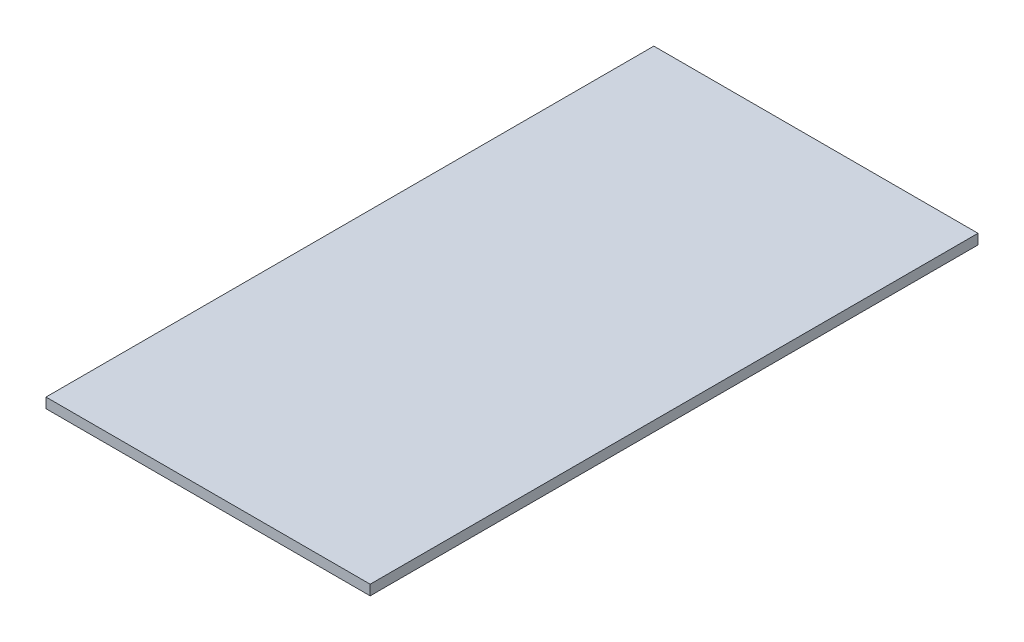
SolidWorks part; units mm, degrees
ref_plane "Front Plane" through (0, 0, 0) normal (0, 0, 1) x (1, 0, 0)
ref_plane "Top Plane" through (0, 0, 0) normal (0, 1, 0) x (1, 0, 0)
ref_plane "Right Plane" through (0, 0, 0) normal (1, 0, 0) x (0, 0, -1)
sketch "Sketch1" plane through (0, 0, 0) normal (0, 1, 0) x (1, 0, 0)
  line L1 (-48, -90) -> (48, -90)
  line L2 (-48, -90) -> (-48, 90)
  line L3 (-48, 90) -> (48, 90)
  line L4 (48, -90) -> (48, 90)
  line L5 (-48, -90) -> (48, 90) construction
  line L6 (-48, 90) -> (48, -90) construction
  point P0 (0, 0)
  dimension "D1" = 180
  dimension "D2" = 96
extrude "Boss-Extrude1" add sketch "Sketch1" along normal blind 3
